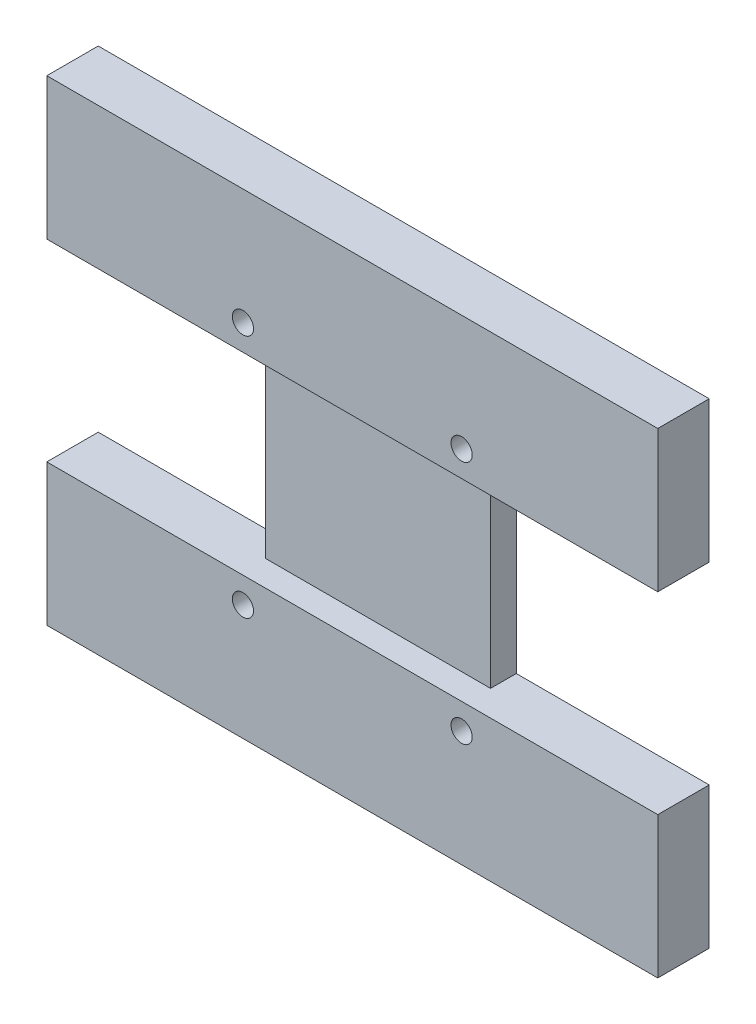
SolidWorks part; units mm, degrees
ref_plane "前视基准面" through (0, 0, 0) normal (0, 0, 1) x (1, 0, 0)
ref_plane "上视基准面" through (0, 0, 0) normal (0, 1, 0) x (1, 0, 0)
ref_plane "右视基准面" through (0, 0, 0) normal (1, 0, 0) x (0, 0, -1)
sketch "草图1" plane through (0, 0, 0) normal (0, 0, 1) x (1, 0, 0)
  line L0 (0, 0) -> (0, 52.1673) construction
  line L1 (0, 0) -> (-33.3035, 0) construction
  line L2 (47.5, 37) -> (-47.5, 37)
  line L3 (-47.5, 37) -> (-47.5, 15)
  line L4 (-47.5, 15) -> (-17.5, 15)
  line L5 (-17.5, 15) -> (-17.5, -15)
  line L6 (17.5, 15) -> (17.5, -15)
  line L7 (47.5, 15) -> (17.5, 15)
  line L8 (47.5, 37) -> (47.5, 15)
  line L15 (47.5, -37) -> (47.5, -15)
  line L16 (47.5, -15) -> (17.5, -15)
  line L17 (-47.5, -15) -> (-17.5, -15)
  line L18 (-47.5, -37) -> (-47.5, -15)
  line L23 (47.5, -37) -> (-47.5, -37)
  point P10 (0, -37)
  point P11 (-17.5, 0)
  point P14 (0, 37)
  point P20 (17.5, 0)
  dimension "D1" = 47.5
  dimension "D2" = 22
  dimension "D3" = 30
  dimension "D4" = 15
extrude "凸台-拉伸1" add sketch "草图1" along normal blind 8
sketch "草图2" plane through (0, 0, 8) normal (0, 0, 1) x (1, 0, 0)
  line L1 (-17.5, 15) -> (17.5, 15)
  line L2 (-17.5, 15) -> (-17.5, -15)
  line L3 (-17.5, -15) -> (17.5, -15)
  line L4 (17.5, 15) -> (17.5, -15)
extrude "切除-拉伸1" cut sketch "草图2" against normal blind 4
hole_wizard "M4 螺纹孔1" positions "3D草图1" profile "草图3" tap size "M4" standard "GB" end condition through all
sketch3d "3D草图1"
  line L0 (0, 0, 0) -> (37.5325, 0, 0) construction
  line L3 (0, 0, 0) -> (0, 30.0599, 0) construction
  point P0 (17, 19, 0)
  dimension "D1" = 17
  dimension "D2" = 19
sketch "草图3" plane through (17, 19, 0) normal (1, 0, 0) x (0, 1, 0)
  line L0 (0, 0) -> (0, 8)
  line L1 (0, 8) -> (1.65, 8)
  line L2 (1.65, 8) -> (1.65, 0.375)
  line L3 (1.65, 0.375) -> (2.025, 0)
  line L5 (2.025, 0) -> (0, 0)
  line L6 (-1.65, 0.375) -> (-2.025, 0) construction
  line L11 (0, -6.35) -> (0, 107.95) construction
  dimension "通孔螺纹孔钻头直径" = 3.3
  dimension "通孔螺纹孔钻头深度" = 8
  dimension "近端锥形沉头孔直径" = 4.05
  dimension "近端锥形沉头孔角度" = 90
cosmetic thread "孔螺蚊线4" parameters "D2"=4
mirror "镜向1" about plane through (0, 0, 0) normal (0, 1, 0) of "M4 螺纹孔1"
mirror "镜向2" about plane through (0, 0, 0) normal (1, 0, 0) of "镜向1", "M4 螺纹孔1"
